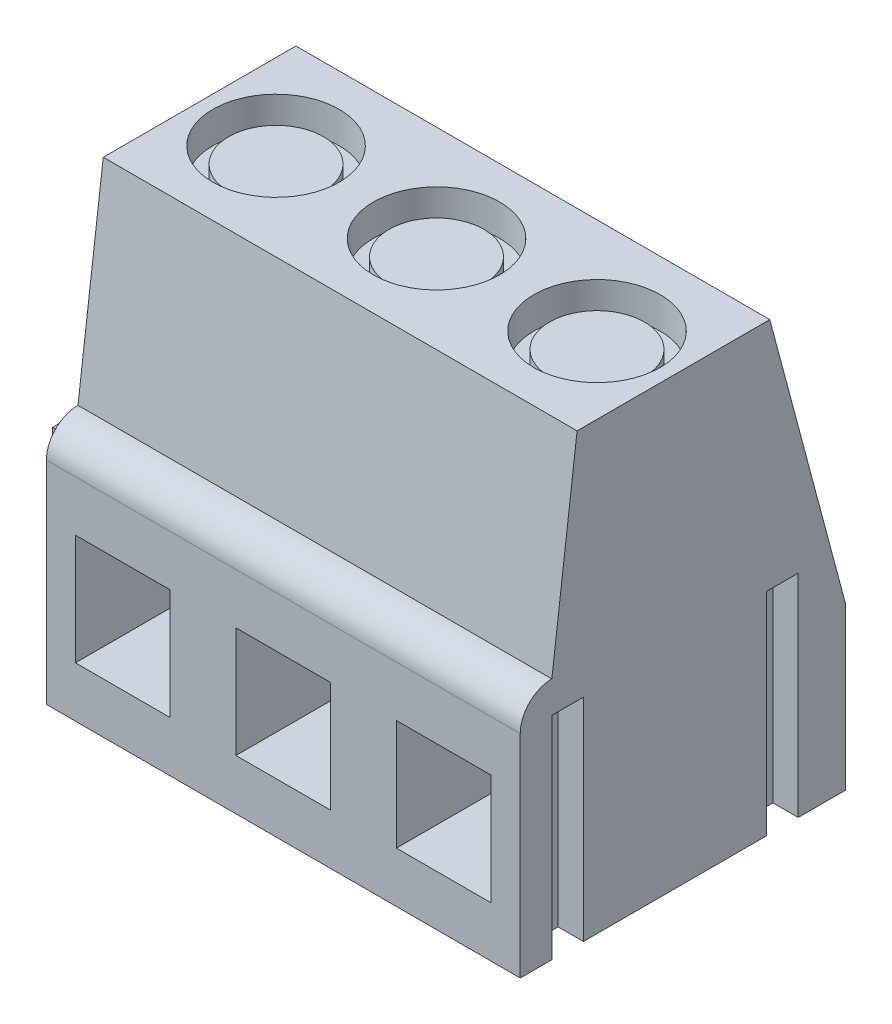
SolidWorks part; units mm, degrees
ref_plane "Front Plane" through (0, 0, 0) normal (0, 0, 1) x (1, 0, 0)
ref_plane "Top Plane" through (0, 0, 0) normal (0, 1, 0) x (1, 0, 0)
ref_plane "Right Plane" through (0, 0, 0) normal (1, 0, 0) x (0, 0, -1)
sketch "Sketch3" plane through (0, 0, 0) normal (1, 0, 0) x (0, 0, -1)
  line L0 (-5.15, 0) -> (5.15, 0)
  line L1 (-3.35, 14.1) -> (2.75, 14.1)
  line L2 (-4.15, 7.7) -> (-3.35, 14.1)
  line L3 (-5.15, 6.7) -> (-5.15, 0)
  line L4 (5.15, 0) -> (5.15, 5.1)
  line L5 (5.15, 5.1) -> (2.75, 14.1)
  arc A0 (-5.15, 6.7) -> (-4.15, 7.7) centre (-4.15, 6.7) cw
  point P4 (0, 0)
  dimension "D4" = 1
  dimension "D1" = 10.3
  dimension "D2" = 6.1
  dimension "D3" = 5.1
  dimension "D5" = 6.4
  dimension "D6" = 14.1
  dimension "D7" = 1.8
  dimension "D8" = 2.4
extrude "Boss-Extrude2" add sketch "Sketch3" along normal blind 15
sketch "Sketch4" plane through (0, 14.1, 0) normal (0, 1, 0) x (1, 0, 0)
  line L0 (0, 2.75) -> (0, -3.35) construction
  line L1 (15, -3.35) -> (0, -3.35) construction
  circle A0 centre (7.5, -0.3) radius 2
  point P4 (0, -0.3)
  point P7 (7.5, -3.35)
  dimension "D1" = 4
extrude "Cut-Extrude1" cut sketch "Sketch4" against normal blind 1
sketch "Sketch5" plane through (0, 13.1, 0) normal (0, 1, 0) x (1, 0, 0)
  circle A2 centre (7.5, -0.3) radius 1.5
  circle A3 centre (7.5, -0.3) radius 1.5
  dimension "D1" = 0.5
extrude "Boss-Extrude3" add sketch "Sketch5" along normal blind 0.5
sketch "Sketch6" plane through (0, 14.1, 0) normal (0, 1, 0) x (1, 0, 0)
  line L0 (0, 2.75) -> (0, -3.35) construction
  line L1 (15, 2.75) -> (0, 2.75) construction
  point P0 (7.5, -0.3)
  point P1 (7.5, -0.3)
  point P5 (7.5, -0.3)
  point P8 (0, -0.3)
  point P11 (7.5, 2.75)
  point P12 (12.58, -0.3)
  point P13 (2.42, -0.3)
  point P14 (7.5, -0.3)
  dimension "D1" = 5.08
  dimension "D2" = 5.08
pattern_sketch "Sketch-Pattern1" of "Cut-Extrude1", "Boss-Extrude3" driven by "Sketch6"
sketch "Sketch7" plane through (0, 0, 5.15) normal (0, 0, 1) x (1, 0, 0)
  line L0 (15, 6.7) -> (15, 0) construction
  line L1 (11.08, 1.6) -> (14.08, 1.6)
  line L2 (11.08, 1.6) -> (11.08, 5.1)
  line L3 (11.08, 5.1) -> (14.08, 5.1)
  line L4 (14.08, 1.6) -> (14.08, 5.1)
  line L5 (11.08, 1.6) -> (14.08, 5.1) construction
  line L6 (11.08, 5.1) -> (14.08, 1.6) construction
  line L7 (15, 6.7) -> (0, 6.7) construction
  point P0 (12.58, 3.35)
  point P7 (15, 3.35)
  point P13 (7.5, 6.7)
  dimension "D1" = 3.5
  dimension "D2" = 3
  dimension "D3" = 5.08
extrude "Cut-Extrude2" cut sketch "Sketch7" against normal blind 6
pattern_linear "LPattern1" count 3 spacing 5.08 along (-1, 0, 0) of "Cut-Extrude2"
sketch "Sketch8" plane through (0, 0, 0) normal (-1, 0, 0) x (0, 0, 1)
  line L0 (5.15, 0) -> (-5.15, 0) construction
  line L1 (4.15, 0) -> (3.15, 0)
  line L2 (4.15, 0) -> (4.15, 6.7)
  line L3 (4.15, 6.7) -> (3.15, 6.7)
  line L4 (3.15, 0) -> (3.15, 6.7)
  line L7 (-5.15, 0) -> (-5.15, 5.1) construction
  line L8 (-2.65, 0) -> (-3.65, 0)
  line L9 (-2.65, 0) -> (-2.65, 6.7)
  line L10 (-2.65, 6.7) -> (-3.65, 6.7)
  line L11 (-3.65, 0) -> (-3.65, 6.7)
  dimension "D1" = 1
  dimension "D2" = 1.5
extrude "Boss-Extrude4" add sketch "Sketch8" along normal blind 0.8
sketch "Sketch9" plane through (15, 0, 0) normal (1, 0, 0) x (0, 0, -1)
  line L4 (2.65, 0) -> (3.65, 0)
  line L5 (3.65, 0) -> (3.65, 6.7)
  line L6 (3.65, 6.7) -> (2.65, 6.7)
  line L7 (2.65, 6.7) -> (2.65, 0)
  line L8 (2.65, 0) -> (3.65, 0)
  line L9 (3.65, 0) -> (3.65, 6.7)
  line L10 (3.65, 6.7) -> (2.65, 6.7)
  line L11 (2.65, 6.7) -> (2.65, 0)
  line L12 (-4.15, 0) -> (-3.15, 0)
  line L13 (-3.15, 0) -> (-3.15, 6.7)
  line L14 (-3.15, 6.7) -> (-4.15, 6.7)
  line L15 (-4.15, 6.7) -> (-4.15, 0)
  line L16 (-4.15, 0) -> (-3.15, 0)
  line L17 (-3.15, 0) -> (-3.15, 6.7)
  line L18 (-3.15, 6.7) -> (-4.15, 6.7)
  line L19 (-4.15, 6.7) -> (-4.15, 0)
  dimension "D1" = 0
  dimension "D2" = 0
extrude "Cut-Extrude3" cut sketch "Sketch9" against normal blind 0.8
sketch "Sketch10" plane through (0, 0, 0) normal (0, -1, 0) x (1, 0, 0)
  line L0 (15, -5.15) -> (0, -5.15) construction
  line L1 (7.15, -0.65) -> (7.85, -0.65)
  line L2 (7.15, -0.65) -> (7.15, 0.05)
  line L3 (7.15, 0.05) -> (7.85, 0.05)
  line L4 (7.85, -0.65) -> (7.85, 0.05)
  line L5 (7.15, -0.65) -> (7.85, 0.05) construction
  line L6 (7.15, 0.05) -> (7.85, -0.65) construction
  line L7 (15, 5.15) -> (0, 5.15) construction
  line L8 (7.5, -0.3) -> (50007.5, -0.3) construction
  line L9 (7.5, -0.3) -> (7.5, 49999.7) construction
  point P0 (7.5, -0.3)
  point P9 (7.5, 5.15)
  dimension "D1" = 5.2
  dimension "D2" = 5.8
  dimension "D3" = 5.45
  dimension "D4" = 4.85
ref_plane "Plane1" through (7.5, 0, 0) normal (1, 0, 0) x (0, 0, -1)
ref_plane "Plane2" through (0, 0, -0.3) normal (0, 0, 1) x (1, 0, 0)
